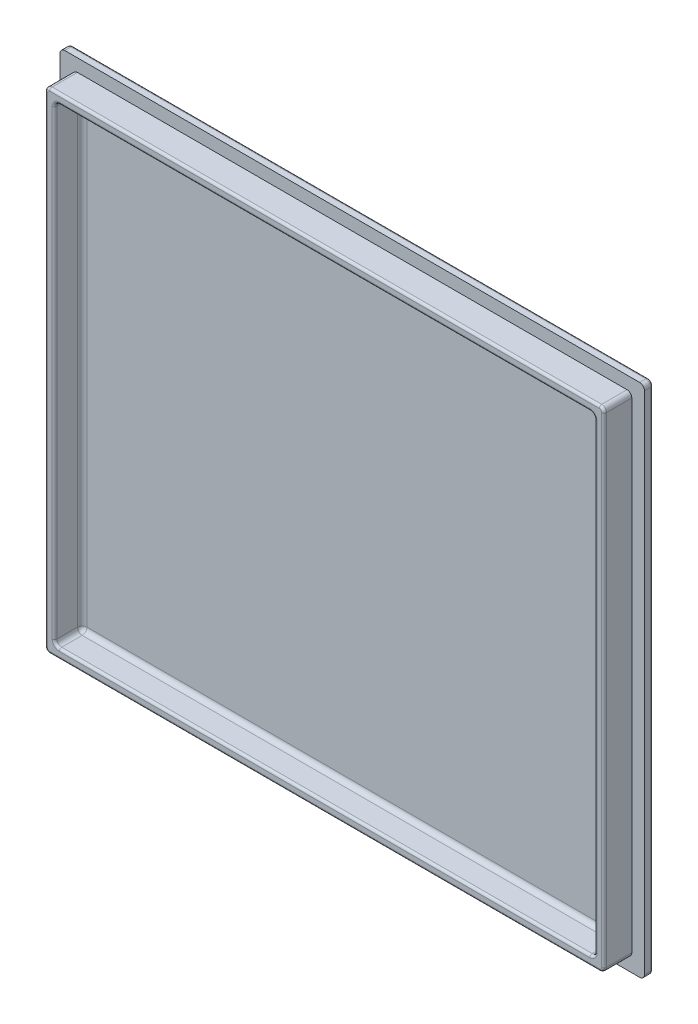
SolidWorks part; units mm, degrees
ref_plane "Front Plane" through (0, 0, 0) normal (0, 0, 1) x (1, 0, 0)
ref_plane "Top Plane" through (0, 0, 0) normal (0, 1, 0) x (1, 0, 0)
ref_plane "Right Plane" through (0, 0, 0) normal (1, 0, 0) x (0, 0, -1)
sketch "Sketch1" plane through (0, 0, 0) normal (0, 0, 1) x (1, 0, 0)
  line L1 (-61.25, 54) -> (61.25, 54)
  line L2 (-61.25, 54) -> (-61.25, -54)
  line L3 (-61.25, -54) -> (61.25, -54)
  line L4 (61.25, 54) -> (61.25, -54)
  line L5 (-61.25, 54) -> (61.25, -54) construction
  line L6 (-61.25, -54) -> (61.25, 54) construction
  point P0 (0, 0)
  dimension "D1" = 108
  dimension "D2" = 122.5
extrude "Boss-Extrude1" add sketch "Sketch1" along normal blind 1.8
sketch "Sketch2" plane through (0, 0, 1.8) normal (0, 0, 1) x (1, 0, 0)
  line L0 (61.25, 54) -> (-61.25, 54) construction
  line L1 (58.6, -51.35) -> (-58.6, -51.35)
  line L2 (58.6, -51.35) -> (58.6, 51.35)
  line L3 (58.6, 51.35) -> (-58.6, 51.35)
  line L4 (-58.6, -51.35) -> (-58.6, 51.35)
  line L5 (58.6, -51.35) -> (-58.6, 51.35) construction
  line L6 (58.6, 51.35) -> (-58.6, -51.35) construction
  line L7 (61.25, -54) -> (61.25, 54) construction
  line L9 (56.6, -49.35) -> (-56.6, -49.35)
  line L10 (56.6, -49.35) -> (56.6, 49.35)
  line L11 (56.6, 49.35) -> (-56.6, 49.35)
  line L12 (-56.6, -49.35) -> (-56.6, 49.35)
  line L13 (56.6, -49.35) -> (-56.6, 49.35) construction
  line L14 (56.6, 49.35) -> (-56.6, -49.35) construction
  point P0 (0, 0)
  point P10 (0, 0)
  dimension "D1" = 2.65
  dimension "D2" = 2.65
  dimension "D3" = 2
  dimension "D4" = 2
extrude "Boss-Extrude2" add sketch "Sketch2" along normal blind 5.8
fillet "Fillet1" radius 1 16 edges at (-61.25, -54, 0.9) (-61.25, 54, 0.9) (61.25, -54, 0.9) (56.6, -49.35, 4.7) (56.6, 49.35, 4.7) (-56.6, 49.35, 4.7) (-56.6, -49.35, 4.7) (-58.6, 51.35, 4.7) (58.6, -51.35, 4.7) (-58.6, -51.35, 4.7) (58.6, 51.35, 4.7) (61.25, 54, 0.9) (0, 49.35, 1.8) (56.6, 0, 1.8) (0, -49.35, 1.8) (-56.6, 0, 1.8)
fillet "Fillet2" radius 0.5 24 edges at (60.9571, -53.7071, 0) (61.25, 0, 0) (60.9571, 53.7071, 0) (0, 54, 0) (-60.9571, 53.7071, 0) (-61.25, 0, 0) (-60.9571, -53.7071, 0) (0, -54, 0) (56.3071, -49.0571, 7.6) (56.6, 0, 7.6) (56.3071, 49.0571, 7.6) (0, 49.35, 7.6) (-56.3071, 49.0571, 7.6) (-56.6, 0, 7.6) (-56.3071, -49.0571, 7.6) (0, -49.35, 7.6) (58.3071, 51.0571, 7.6) (58.6, 0, 7.6) (58.3071, -51.0571, 7.6) (0, -51.35, 7.6) (-58.3071, -51.0571, 7.6) (-58.6, 0, 7.6) (-58.3071, 51.0571, 7.6) (0, 51.35, 7.6)
sketch "Sketch3" plane through (0, 0, 0) normal (0, 0, -1) x (-1, 0, 0)
  line L0 (-61.25, 0) -> (61.25, 0) construction
  line L1 (-61.25, -53) -> (-61.25, 53) construction
  line L2 (61.25, 53) -> (61.25, -53) construction
  line L3 (-60.75, 9) -> (60.75, 9) construction
  line L4 (-60.75, 53) -> (-60.75, -53) construction
  line L5 (60.75, -53) -> (60.75, 53) construction
  text T0 "JOULEMETER\r\n100V DC\r\n100A DC" font "Arial Rounded MT Bold" height 7.5
  dimension "D1" = 9
extrude "Cut-Extrude1" cut sketch "Sketch3" against normal blind 0.4
